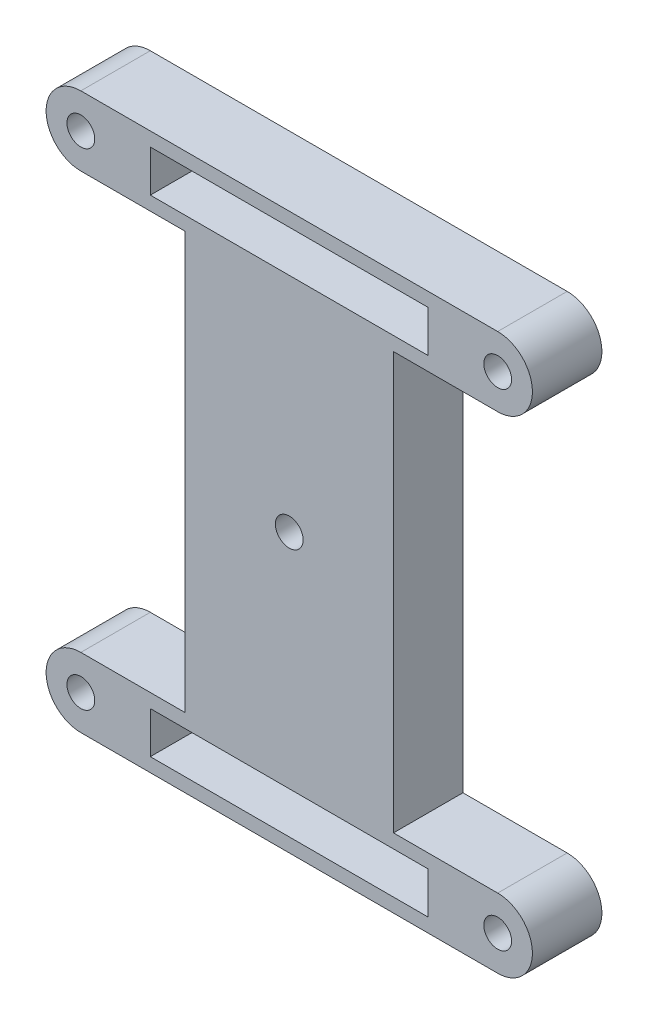
SolidWorks part; units mm, degrees
ref_plane "Front Plane" through (0, 0, 0) normal (0, 0, 1) x (1, 0, 0)
ref_plane "Top Plane" through (0, 0, 0) normal (0, 1, 0) x (1, 0, 0)
ref_plane "Right Plane" through (0, 0, 0) normal (1, 0, 0) x (0, 0, -1)
sketch "Sketch1" plane through (0, 0, 0) normal (0, 0, 1) x (1, 0, 0)
  line L0 (-15, 17.5) -> (15, 17.5) construction
  line L1 (7.5, 15) -> (15, 15)
  line L2 (-7.5, 15) -> (-7.5, -15)
  line L3 (-7.5, -15) -> (7.5, -15) construction
  line L4 (7.5, 15) -> (7.5, -15)
  line L5 (-7.5, 15) -> (7.5, -15) construction
  line L6 (-7.5, -15) -> (7.5, 15) construction
  line L7 (-15, 20) -> (15, 20)
  line L8 (-15, 15) -> (-7.5, 15)
  line L9 (-32.3549, 0) -> (39.4021, 0) construction
  line L10 (-15, -17.5) -> (15, -17.5) construction
  line L11 (-15, -15) -> (-7.5, -15)
  line L12 (-15, -20) -> (15, -20)
  line L13 (7.5, -15) -> (15, -15)
  arc A0 (-15, 20) -> (-15, 15) centre (-15, 17.5) ccw
  arc A1 (15, 15) -> (15, 20) centre (15, 17.5) ccw
  circle A2 centre (-15, 17.5) radius 1
  circle A3 centre (15, 17.5) radius 1
  circle A4 centre (15, -17.5) radius 1
  circle A5 centre (-15, -17.5) radius 1
  arc A6 (15, -15) -> (15, -20) centre (15, -17.5) cw
  arc A7 (-15, -20) -> (-15, -15) centre (-15, -17.5) cw
  point P0 (0, 0)
  point P8 (0, 20)
  point P25 (0, -20)
  dimension "D3" = 2.5
  dimension "D6" = 2.5
  dimension "D7" = 2
  dimension "D8" = 2
  dimension "D1" = 30
  dimension "D2" = 15
  dimension "D4" = 30
  dimension "D5" = 7.5
extrude "Boss-Extrude2" add sketch "Sketch1" along normal mid plane 5
sketch "Sketch2" plane through (0, 0, 2.5) normal (0, 0, 1) x (1, 0, 0)
  line L0 (0, 25.1089) -> (0, -5.5376) construction
  line L1 (-10, 19) -> (10, 19)
  line L2 (-10, 19) -> (-10, 16)
  line L3 (-10, 16) -> (10, 16)
  line L4 (10, 19) -> (10, 16)
  line L5 (15, 20) -> (-15, 20) construction
  line L6 (-23.3833, 0) -> (29.3707, 0) construction
  line L7 (10, -19) -> (10, -16)
  line L8 (-10, -16) -> (10, -16)
  line L9 (-10, -19) -> (-10, -16)
  line L10 (-10, -19) -> (10, -19)
  circle A0 centre (0, 0) radius 1
  dimension "D1" = 2
  dimension "D2" = 3
  dimension "D3" = 20
  dimension "D4" = 1
extrude "Cut-Extrude1" cut sketch "Sketch2" against normal through all
